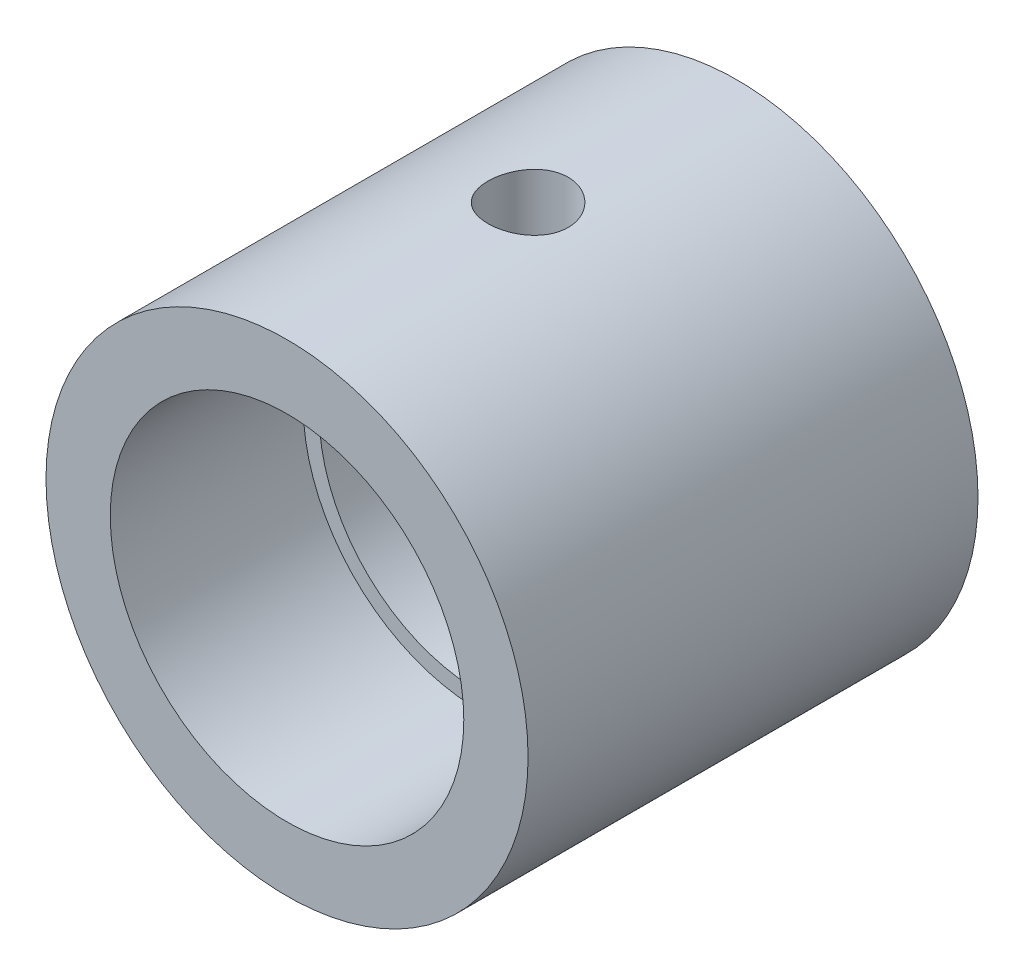
SolidWorks part; units mm, degrees
ref_plane "Front Plane" through (0, 0, 0) normal (0, 0, 1) x (1, 0, 0)
ref_plane "Top Plane" through (0, 0, 0) normal (0, 1, 0) x (1, 0, 0)
ref_plane "Right Plane" through (0, 0, 0) normal (1, 0, 0) x (0, 0, -1)
sketch "Sketch1" plane through (0, 0, 0) normal (0, 0, 1) x (1, 0, 0)
  circle A0 centre (0, 0) radius 15
  dimension "D1" = 30
extrude "Boss-Extrude1" add sketch "Sketch1" along normal blind 27
hole_wizard "CBORE for M6 Hex Head Bolt1" positions "Sketch2" profile "Sketch3" counterbore size "M6" standard "ISO" end condition through all
sketch "Sketch2" plane through (0, 0, 27) normal (0, 0, 1) x (1, 0, 0)
  point P0 (0, 0)
sketch "Sketch3" plane through (0, 0, 27) normal (1, 0, 0) x (0, -1, 0)
  line L0 (0, 0) -> (0, 27)
  line L1 (0, 27) -> (10, 27)
  line L3 (10, 27) -> (10, 12)
  line L4 (10, 12) -> (11, 12)
  line L5 (11, 12) -> (11, 0)
  line L7 (11, 0) -> (0, 0)
  line L11 (0, -6.35) -> (0, 107.95) construction
  dimension "Thru Hole Dia." = 20
  dimension "Thru Hole Depth" = 27
  dimension "C'Bore Dia." = 22
  dimension "C'Bore Depth" = 12
sketch "Sketch4" plane through (0, 0, 0) normal (0, 1, 0) x (1, 0, 0)
  circle A0 centre (0, -12) radius 2.5
  dimension "D1" = 5
  dimension "D2" = 12
sketch "Sketch5" plane through (0, 0, 0) normal (0, 0, -1) x (-1, 0, 0)
  circle A0 centre (0, 0) radius 15
extrude "Boss-Extrude2" add sketch "Sketch5" along normal blind 1
extrude "Cut-Extrude1" cut sketch "Sketch4" against normal through all both and the other way through all
